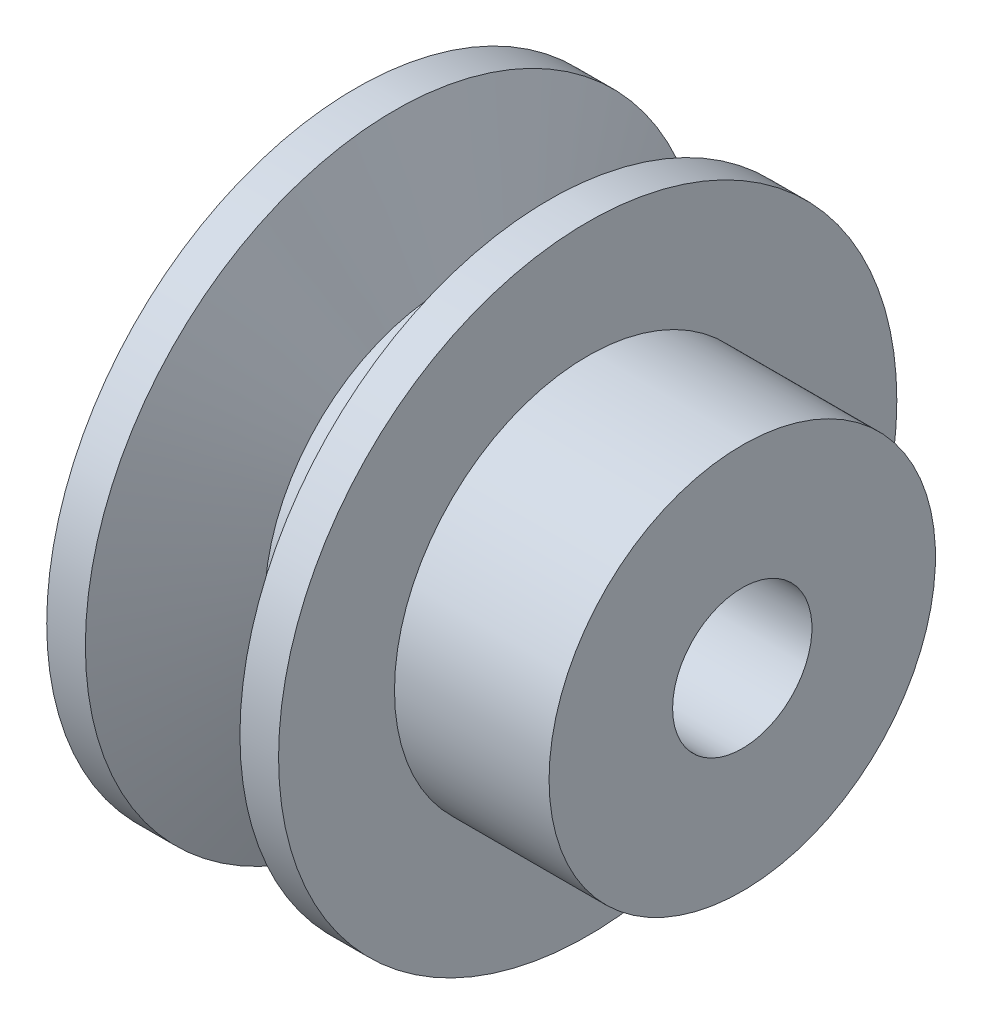
SolidWorks part; units mm, degrees
ref_plane "Front Plane" through (0, 0, 0) normal (0, 0, 1) x (1, 0, 0)
ref_plane "Top Plane" through (0, 0, 0) normal (0, 1, 0) x (1, 0, 0)
ref_plane "Right Plane" through (0, 0, 0) normal (1, 0, 0) x (0, 0, -1)
sketch "Sketch1" plane through (0, 0, 0) normal (0, 0, 1) x (1, 0, 0)
  line L0 (-33.7412, 0) -> (40.019, 0) construction
  line L1 (-28.7412, 9.0147) -> (16.2588, 9.0147)
  line L2 (16.2588, 9.0147) -> (16.2588, 25)
  line L3 (16.2588, 25) -> (-3.7412, 25)
  line L4 (-3.7412, 25) -> (-3.7412, 40)
  line L5 (-3.7412, 40) -> (-8.7412, 40)
  line L6 (-8.7412, 40) -> (-15.5363, 23.5951)
  line L7 (-15.5363, 23.5951) -> (-21.9461, 23.5951)
  line L8 (-21.9461, 23.5951) -> (-28.7412, 40)
  line L9 (-28.7412, 40) -> (-33.7412, 40)
  line L10 (-33.7412, 40) -> (-33.7412, 20)
  line L11 (-33.7412, 20) -> (-28.7412, 9.0147)
  dimension "D1" = 20
  dimension "D2" = 45
  dimension "D3" = 25
  dimension "D4" = 40
  dimension "D5" = 5
  dimension "D6" = 5
  dimension "D7" = 5
  dimension "D8" = 20
  dimension "D9" = 20
  dimension "D10" = 40
  dimension "D11" = 16.2588
  dimension "D12" = 15.5363
  dimension "D13" = 21.9461
  dimension "D14" = 9.0147
revolve "Revolve1" add sketch "Sketch1" angle 360 about L0
